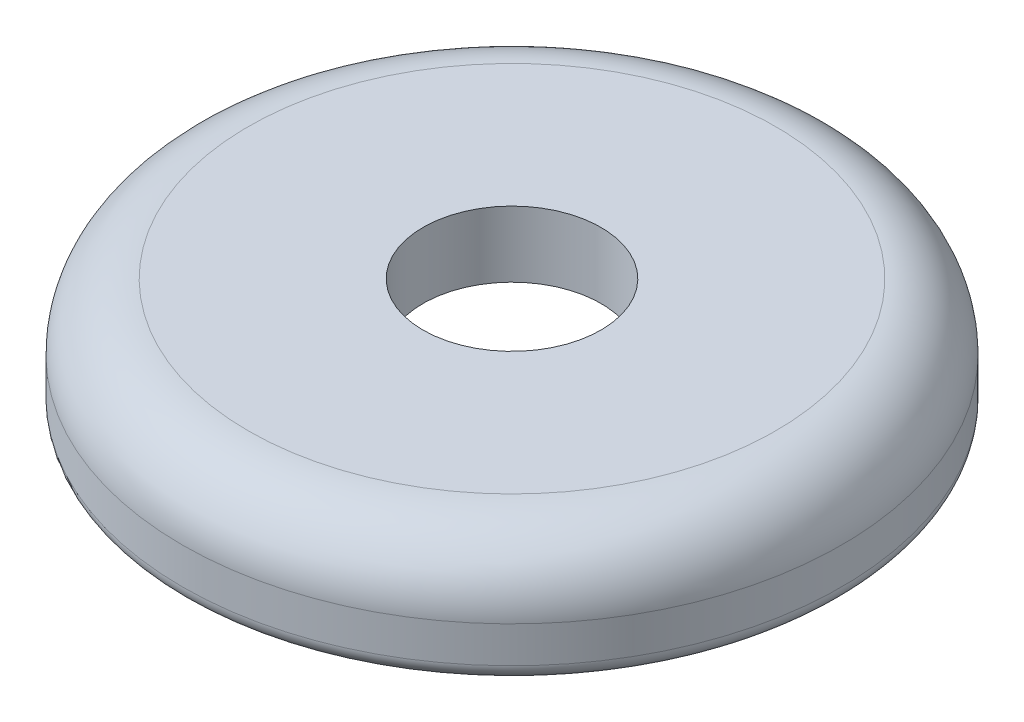
SolidWorks part; units mm, degrees
ref_plane "Front Plane" through (0, 0, 0) normal (0, 0, 1) x (1, 0, 0)
ref_plane "Top Plane" through (0, 0, 0) normal (0, 1, 0) x (1, 0, 0)
ref_plane "Right Plane" through (0, 0, 0) normal (1, 0, 0) x (0, 0, -1)
sketch "Sketch1" plane through (0, 0, 0) normal (0, 1, 0) x (1, 0, 0)
  line L1 (7.479, 0) -> (3.7395, 6.477)
  line L2 (3.7395, 6.477) -> (-3.7395, 6.477)
  line L3 (-3.7395, 6.477) -> (-7.479, 0)
  line L4 (-7.479, 0) -> (-3.7395, -6.477)
  line L5 (-3.7395, -6.477) -> (3.7395, -6.477)
  line L6 (3.7395, -6.477) -> (7.479, 0)
  circle A0 centre (0, 0) radius 12.7
  circle A1 centre (0, 0) radius 6.477 construction
  dimension "D2" = 25.4
  dimension "D1" = 12.954
extrude "Boss-Extrude1" add sketch "Sketch1" along normal blind 2.032
sketch "Sketch2" plane through (0, 2.032, 0) normal (0, 1, 0) x (1, 0, 0)
  circle A0 centre (0, 0) radius 3.429
  circle A1 centre (0, 0) radius 12.7
  circle A2 centre (0, 0) radius 12.7 construction
  dimension "D1" = 6.858
extrude "Boss-Extrude2" add sketch "Sketch2" along normal blind 2.54
fillet "Fillet1" radius 2.54 1 edges at (0, 4.572, 12.7)
fillet "Fillet2" radius 0.635 7 edges at (0, 0, 6.477) (-5.6092, 0, 3.2385) (-5.6092, 0, -3.2385) (0, 0, -6.477) (5.6092, 0, -3.2385) (5.6092, 0, 3.2385) (0, 0, 12.7)
